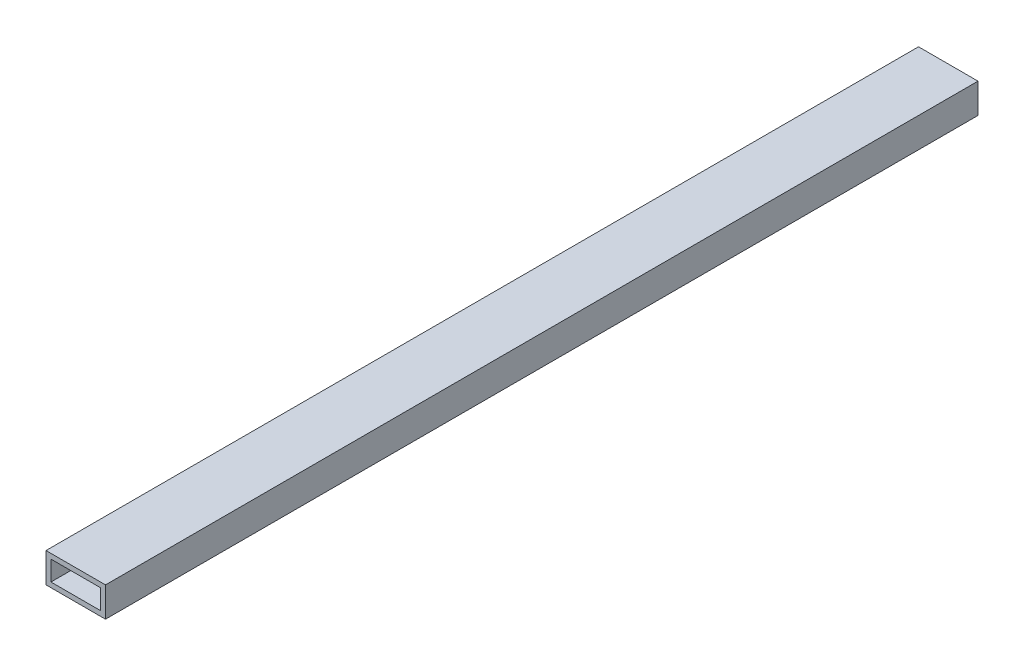
SolidWorks part; units mm, degrees
ref_plane "Front Plane" through (0, 0, 0) normal (0, 0, 1) x (1, 0, 0)
ref_plane "Top Plane" through (0, 0, 0) normal (0, 1, 0) x (1, 0, 0)
ref_plane "Right Plane" through (0, 0, 0) normal (1, 0, 0) x (0, 0, -1)
sketch "Sketch1" plane through (0, 0, 0) normal (0, 0, 1) x (1, 0, 0)
  line L1 (0, 0) -> (38.1, 0)
  line L2 (0, 0) -> (0, 19.05)
  line L3 (0, 19.05) -> (38.1, 19.05)
  line L4 (38.1, 0) -> (38.1, 19.05)
  dimension "D1" = 19.05
  dimension "D2" = 38.1
extrude "Extrude-Thin1" add sketch "Sketch1" along normal blind 558.8 thin thin type one direction reverse wall 3.175
